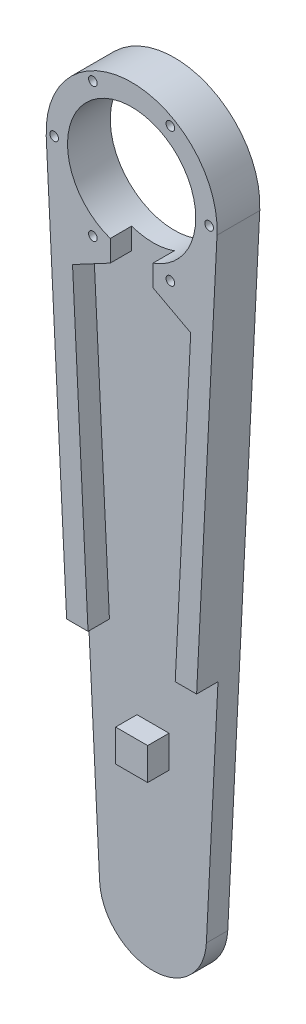
SolidWorks part; units mm, degrees
ref_plane "Front Plane" through (0, 0, 0) normal (0, 0, 1) x (1, 0, 0)
ref_plane "Top Plane" through (0, 0, 0) normal (0, 1, 0) x (1, 0, 0)
ref_plane "Right Plane" through (0, 0, 0) normal (1, 0, 0) x (0, 0, -1)
sketch "Sketch1" plane through (0, 0, 0) normal (0, 0, 1) x (1, 0, 0)
  line L0 (-1000, 0) -> (49000, 0) construction
  line L1 (0, -1000) -> (0, 49000) construction
  circle A0 centre (0, 0) radius 40
  circle A1 centre (0, 0) radius 30
  circle A2 centre (0, 0) radius 36.25 construction
  point P4 (0, 36.25)
  dimension "D1" = 80
  dimension "D2" = 60
  dimension "D3" = 72.5
extrude "Boss-Extrude1" add sketch "Sketch1" against normal blind 10
hole_wizard "M4x0.7 Tapped Hole1" positions "Sketch7" profile "Sketch8" tap size "M4x0.7" standard "ANSI Metric" end condition through all
sketch "Sketch7" plane through (0, 0, 0) normal (0, 0, 1) x (1, 0, 0)
  line L0 (0, 0) -> (36.25, 0) construction
  circle A0 centre (0, 0) radius 36.25 construction
  point P9 (36.25, 0)
  point P15 (0, 0)
cosmetic thread "Hole Thread1" parameters "D2"=4
sketch "Sketch8" plane through (36.25, 0, 0) normal (1, 0, 0) x (0, -1, 0)
  line L0 (0, 0) -> (0, 10)
  line L1 (0, 10) -> (1.65, 10)
  line L2 (1.65, 10) -> (1.65, 0.375)
  line L3 (1.65, 0.375) -> (2.025, 0)
  line L5 (2.025, 0) -> (0, 0)
  line L6 (-1.65, 0.375) -> (-2.025, 0) construction
  line L11 (0, -6.35) -> (0, 107.95) construction
  dimension "Thru Tap Drill Dia." = 3.3
  dimension "Thru Tap Drill Depth" = 10
  dimension "Near C'Sink Dia." = 4.05
  dimension "Near C'Sink Angle" = 90
sketch "Sketch9" plane through (0, 0, 0) normal (1, 0, 0) x (0, 0, -1)
  line L0 (-1000, 0) -> (49000, 0) construction
pattern_circular "CirPattern1" count 6 over 360 about axis through (0, 0, 0) along (0, 0, 1) of "M4x0.7 Tapped Hole1"
cosmetic thread "Hole Thread2" parameters "D2"=4
cosmetic thread "Hole Thread3" parameters "D2"=4
cosmetic thread "Hole Thread4" parameters "D2"=4
cosmetic thread "Hole Thread5" parameters "D2"=4
cosmetic thread "Hole Thread6" parameters "D2"=4
cosmetic thread "Hole Thread7" parameters "D2"=4
cosmetic thread "Hole Thread8" parameters "D2"=4
cosmetic thread "Hole Thread9" parameters "D2"=4
cosmetic thread "Hole Thread10" parameters "D2"=4
cosmetic thread "Hole Thread11" parameters "D2"=4
cosmetic thread "Hole Thread12" parameters "D2"=4
sketch "Sketch14" plane through (0, 0, 0) normal (0, 0, 1) x (1, 0, 0)
  line L0 (-1000, 0) -> (49000, 0) construction
  line L1 (0, -1000) -> (0, 49000) construction
  line L2 (-1000, -300) -> (49000, -300) construction
  line L3 (-39.95, -2) -> (-24.9687, -301.25)
  line L4 (39.95, -2) -> (24.9687, -301.25)
  circle A0 centre (0, -300) radius 25
  circle A1 centre (0, 0) radius 40 construction
  circle A2 centre (0, 0) radius 40
  dimension "D2" = 50
  dimension "D1" = 300
extrude "Boss-Extrude5" add sketch "Sketch14" against normal blind 10 contours A2 L3 A0 L4 | A0
sketch "Sketch15" plane through (0, 0, 0) normal (0, 0, 1) x (1, 0, 0)
  line L0 (0, -1000) -> (0, 49000) construction
  line L1 (10, -28.2843) -> (10, -38.2843)
  line L2 (-39.95, -2) -> (-24.9687, -301.25)
  line L3 (24.9687, -301.25) -> (39.95, -2)
  line L4 (-39.95, -2) -> (-24.9687, -301.25)
  line L5 (24.9687, -301.25) -> (39.95, -2)
  line L6 (10, -38.2843) -> (10, -28.2843)
  line L7 (10, -38.2843) -> (27.6501, -47.6904)
  line L8 (27.6501, -47.6904) -> (20.391, -192.6904)
  line L9 (20.391, -192.6904) -> (7.5, -225)
  line L10 (7.5, -225) -> (-7.5, -225)
  line L11 (-20.391, -192.6904) -> (-7.5, -225)
  line L12 (-27.6501, -47.6904) -> (-20.391, -192.6904)
  line L13 (-10, -38.2843) -> (-27.6501, -47.6904)
  line L14 (-10, -28.2843) -> (-10, -38.2843)
  line L15 (20.391, -192.6904) -> (30.4035, -192.6904)
  line L16 (-20.391, -192.6904) -> (-30.4035, -192.6904)
  line L17 (-7.5, -225) -> (7.5, -225)
  line L18 (-7.5, -225) -> (-7.5, -240)
  line L19 (7.5, -225) -> (7.5, -240)
  line L20 (-7.5, -240) -> (7.5, -240)
  circle A1 centre (0, 0) radius 30 construction
  arc A2 (39.95, -2) -> (-39.95, -2) centre (0, 0) ccw
  arc A3 (-24.9687, -301.25) -> (24.9687, -301.25) centre (0, -300) ccw
  arc A4 (39.95, -2) -> (-39.95, -2) centre (0, 0) ccw
  arc A5 (-24.9687, -301.25) -> (24.9687, -301.25) centre (0, -300) ccw
  circle A6 centre (0, 0) radius 30
  point P22 (0, -225)
  circle M17 centre (0, 0) radius 30
  arc M18 (39.95, -2) -> (-39.95, -2) centre (0, 0) ccw
  line M19 (-39.95, -2) -> (-24.9687, -301.25)
  circle M28 centre (18.125, 31.3934) radius 2.025
  circle M29 centre (-18.125, 31.3934) radius 2.025
  circle M30 centre (-36.25, 0) radius 2.025
  circle M31 centre (-18.125, -31.3934) radius 2.025
  circle M32 centre (18.125, -31.3934) radius 2.025
  circle M33 centre (36.25, 0) radius 2.025
  dimension "D2" = 75
  dimension "D3" = 10
  dimension "D4" = 10
  dimension "D5" = 10
  dimension "D6" = 145
  dimension "D7" = 20
  dimension "D8" = 7.5
  dimension "D9" = 15
  dimension "D1" = 0
extrude "Boss-Extrude7" add sketch "Sketch15" along normal blind 10 contours L0 L20 L19 L10 | L20 L0 L17 L18 | L0 A6 L1 L7 L8 L15 L5 M18 M33 M32 M28 | L0 A4 L16 L12 L13 L14 M17 M19 M30 M31 M29
